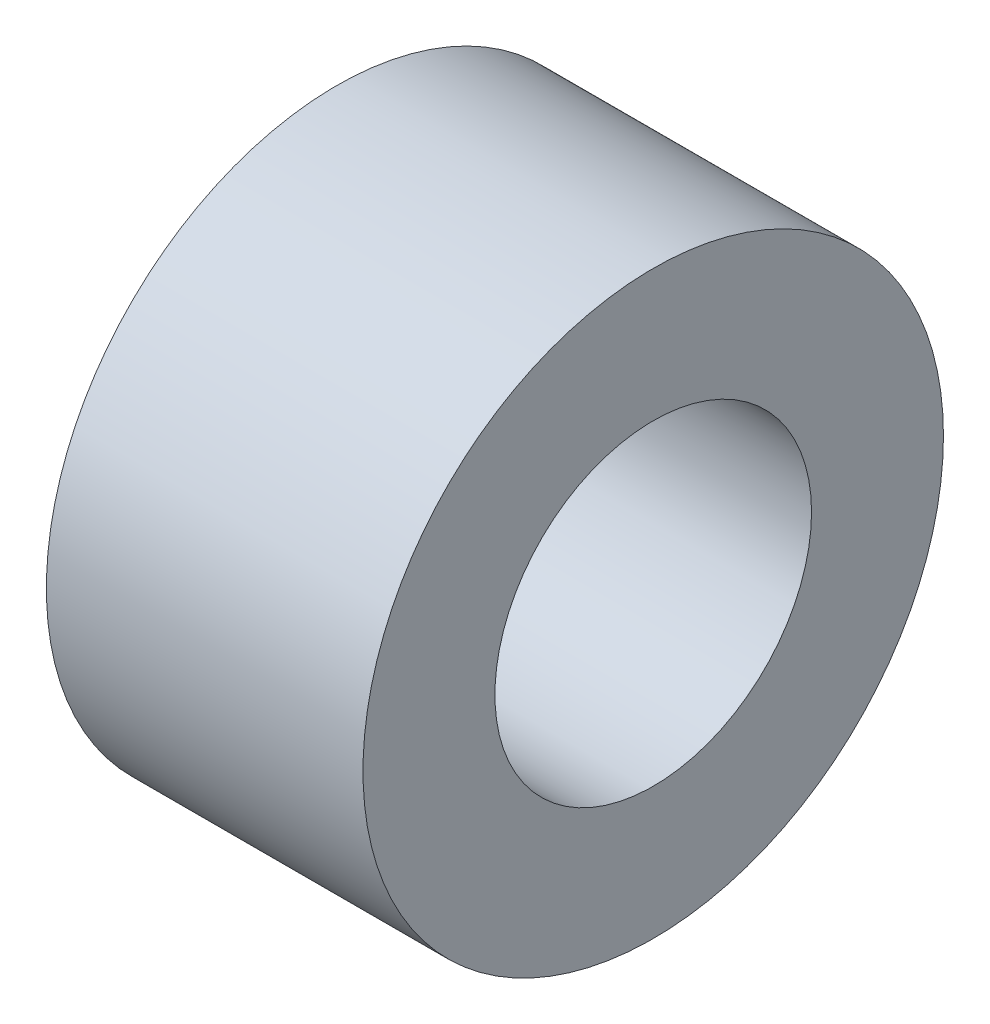
SolidWorks part; units mm, degrees
ref_plane "前视基准面" through (0, 0, 0) normal (0, 0, 1) x (1, 0, 0)
ref_plane "上视基准面" through (0, 0, 0) normal (0, 1, 0) x (1, 0, 0)
ref_plane "右视基准面" through (0, 0, 0) normal (1, 0, 0) x (0, 0, -1)
sketch "草图1" plane through (0, 0, 0) normal (1, 0, 0) x (0, 0, -1)
  circle A0 centre (0, 0) radius 3
  circle A1 centre (0, 0) radius 5.5
extrude "凸台-拉伸1" add sketch "草图1" along normal blind 6
